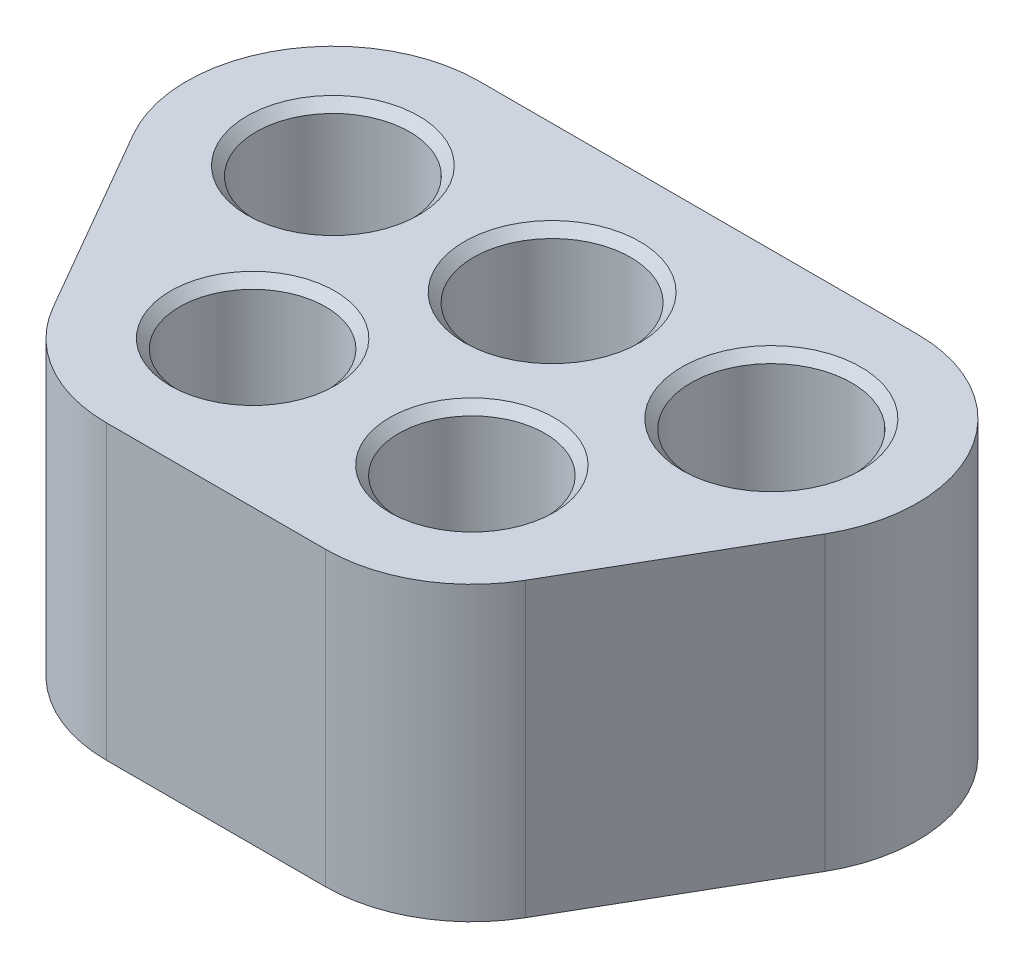
SolidWorks part; units mm, degrees
ref_plane "Front Plane" through (0, 0, 0) normal (0, 0, 1) x (1, 0, 0)
ref_plane "Top Plane" through (0, 0, 0) normal (0, 1, 0) x (1, 0, 0)
ref_plane "Right Plane" through (0, 0, 0) normal (1, 0, 0) x (0, 0, -1)
sketch "Sketch1" plane through (0, 0, 0) normal (0, 1, 0) x (1, 0, 0)
  line L0 (6, 0) -> (12, 0) construction
  line L1 (9, 0) -> (9, -5.1962) construction
  line L2 (0, 0) -> (6, 0) construction
  line L3 (3, 0) -> (3, -5.1962) construction
  line L4 (0, 0) -> (3, -5.1962) construction
  line L5 (-6.9282, 4) -> (0.6906, -9.1962)
  line L6 (0.6906, -9.1962) -> (11.3094, -9.1962)
  line L7 (11.3094, -9.1962) -> (18.9282, 4)
  line L8 (18.9282, 4) -> (-6.9282, 4)
  circle A0 centre (0, 0) radius 2.1
  circle A1 centre (6, 0) radius 2.15
  circle A2 centre (12, 0) radius 2.2
  circle A3 centre (3, -5.1962) radius 2
  circle A4 centre (9, -5.1962) radius 2
  point P13 (-6, 3.419)
  point P18 (0, 0)
  point P19 (-1.2149, 3.3007)
  dimension "D1" = 4.2
  dimension "D2" = 4.3
  dimension "D3" = 4.4
  dimension "D4" = 4
  dimension "D5" = 4
  dimension "D8" = 6
  dimension "D6" = 6
  dimension "D7" = 6
  dimension "D9" = 4
  dimension "D10" = 4
  dimension "D11" = 4
  dimension "D12" = 4
  dimension "D13" = 4
  dimension "D14" = 4
extrude "Boss-Extrude1" add sketch "Sketch1" along normal blind 8
fillet "Fillet1" radius 4 4 edges at (-6.9282, 4, -4) (18.9282, 4, -4) (11.3094, 4, 9.1962) (0.6906, 4, 9.1962)
chamfer "Chamfer1" distance 0.25 angle 45 5 edges at (3, 8, 7.1962) (9, 8, 7.1962) (12, 8, 2.2) (6, 8, 2.15) (0, 8, 2.1)
